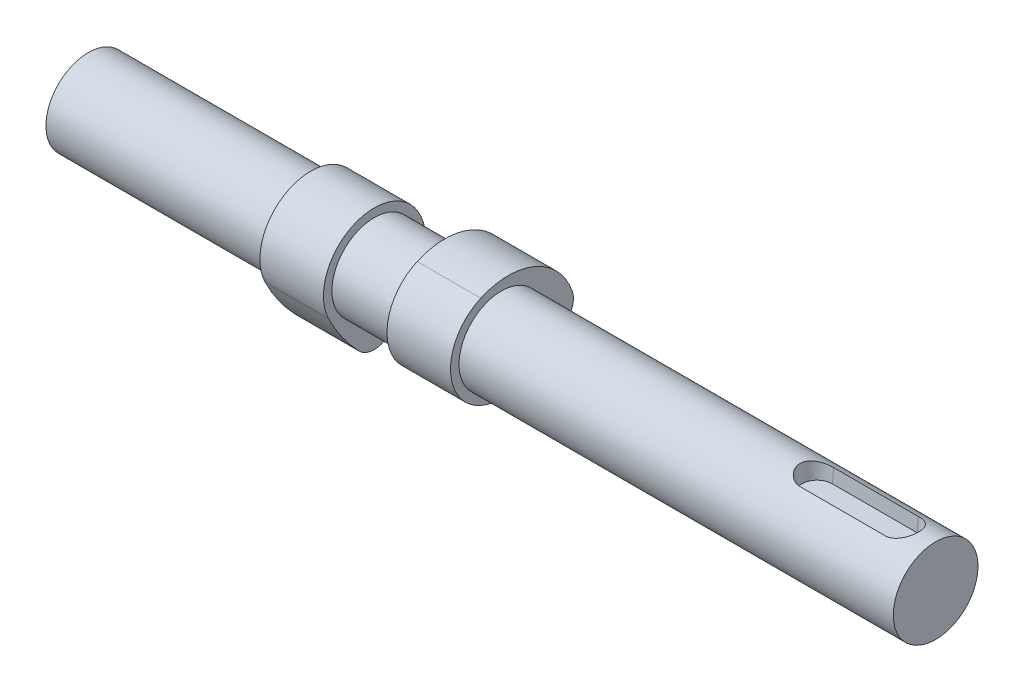
SolidWorks part; units mm, degrees
ref_plane "Front Plane" through (0, 0, 0) normal (0, 0, 1) x (1, 0, 0)
ref_plane "Top Plane" through (0, 0, 0) normal (0, 1, 0) x (1, 0, 0)
ref_plane "Right Plane" through (0, 0, 0) normal (1, 0, 0) x (0, 0, -1)
sketch "Sketch2" plane through (0, 0, 0) normal (1, 0, 0) x (0, 0, -1)
  circle A0 centre (0, 0) radius 10
  dimension "D1" = 20
extrude "Boss-Extrude1" add sketch "Sketch2" along normal blind 125 and the other way blind 75
sketch "Sketch3" plane through (0, 0, 0) normal (1, 0, 0) x (0, 0, -1)
  arc A0 (-4.8671, 10.9687) -> (5.3062, -10.7631) centre (0, 0) ccw
  arc A1 (-4.8671, 10.9687) -> (16.7127, 1.6619) centre (1.6224, -3.6562) cw
  arc A2 (5.3062, -10.7631) -> (15.4795, -3.5877) centre (-12.3812, 25.1139) ccw
  arc A3 (16.7127, 1.6619) -> (15.4795, -3.5877) centre (11.997, 0) cw
  dimension "D1" = 5
  dimension "D2" = 24
  dimension "D3" = 40
  dimension "D4" = 16
  dimension "D5" = 12.5
extrude "Boss-Extrude2" add sketch "Sketch3" along normal mid plane 15 from offset 15 separate body
mirror "Mirror1" about plane through (0, 0, 0) normal (1, 0, 0) of bodies 102
move or copy body "Body-Move/Copy1" bodies to move or copy 103 copy no rotation origin (0, 0, 0) rotation axis (-1, 0, 0) rotation angle 90 parameters "Angle Around Edge"=270
sketch "Sketch4" plane through (0, 0, 0) normal (0, 1, 0) x (1, 0, 0)
  line L0 (125, 0) -> (89.2137, 0) construction
  line L1 (125, -10) -> (125, 10) construction
  line L2 (97, 0) -> (117, 0) construction
  line L3 (97, 4) -> (117, 4)
  line L4 (97, -4) -> (117, -4)
  arc A0 (97, 4) -> (97, -4) centre (97, 0) ccw
  arc A1 (117, -4) -> (117, 4) centre (117, 0) ccw
  point P7 (107, 0)
  dimension "D1" = 4
  dimension "D2" = 20
  dimension "D3" = 8
extrude "Cut-Extrude1" cut sketch "Sketch4" against normal blind 4 draft 5 from offset 10
